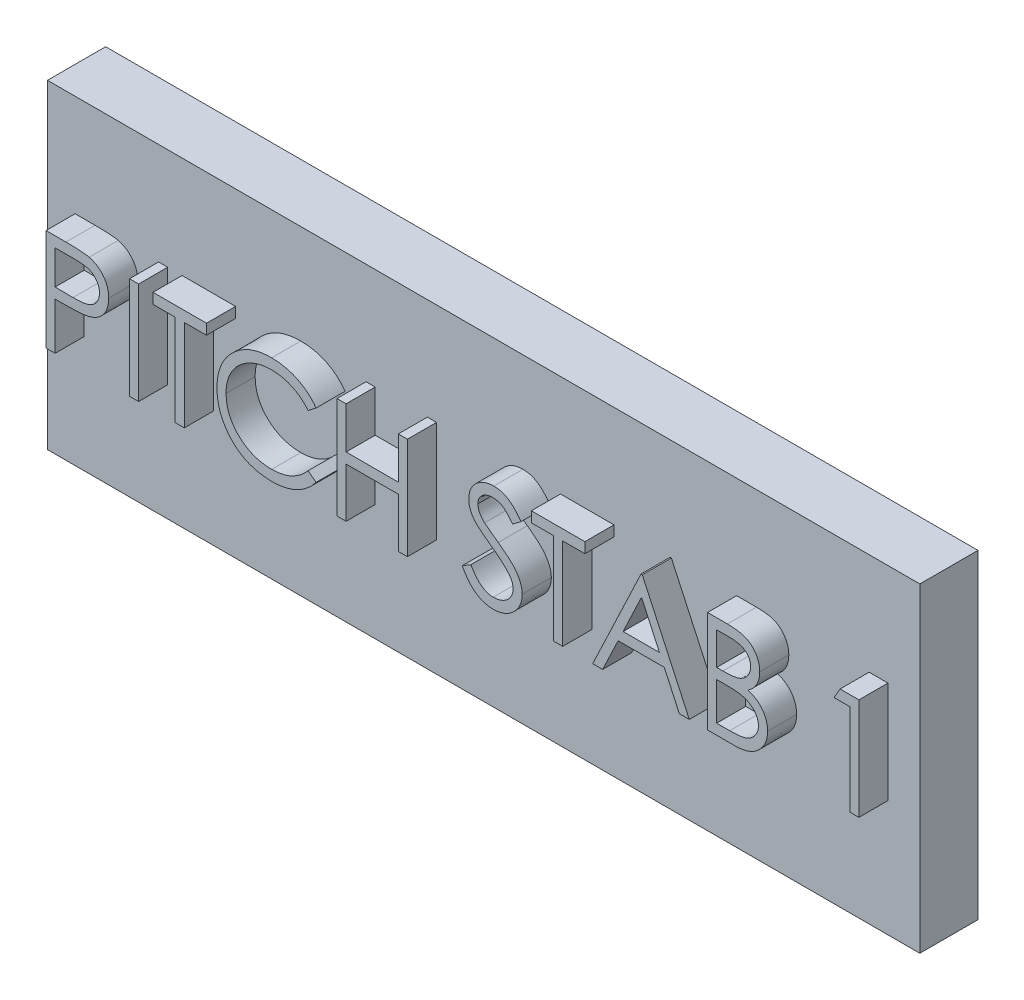
SolidWorks part; units mm, degrees
ref_plane "Front Plane" through (0, 0, 0) normal (0, 0, 1) x (1, 0, 0)
ref_plane "Top Plane" through (0, 0, 0) normal (0, 1, 0) x (1, 0, 0)
ref_plane "Right Plane" through (0, 0, 0) normal (1, 0, 0) x (0, 0, -1)
sketch "Sketch1" plane through (0, 0, 0) normal (0, 0, 1) x (1, 0, 0)
  line L1 (-51.24, 31.58) -> (-21.24, 31.58)
  line L2 (-51.24, 31.58) -> (-51.24, 20.58)
  line L3 (-51.24, 20.58) -> (-21.24, 20.58)
  line L4 (-21.24, 31.58) -> (-21.24, 20.58)
  dimension "D1" = 30
  dimension "D2" = 11
extrude "Boss-Extrude1" add sketch "Sketch1" along normal blind 2
sketch "Sketch2" plane through (0, 0, 2) normal (0, 0, 1) x (1, 0, 0)
  line L0 (-51.24, 31.58) -> (-51.24, 20.58) construction
  line L2 (-21.24, 31.58) -> (-51.24, 31.58) construction
  text T0 "PITCH STAB 1"
  point P3 (0, 0)
  point P4 (0, 0)
  point P6 (0, 0)
  dimension "D1" = 0.5
  dimension "D2" = 7
extrude "Boss-Extrude2" add sketch "Sketch2" along normal blind 1
